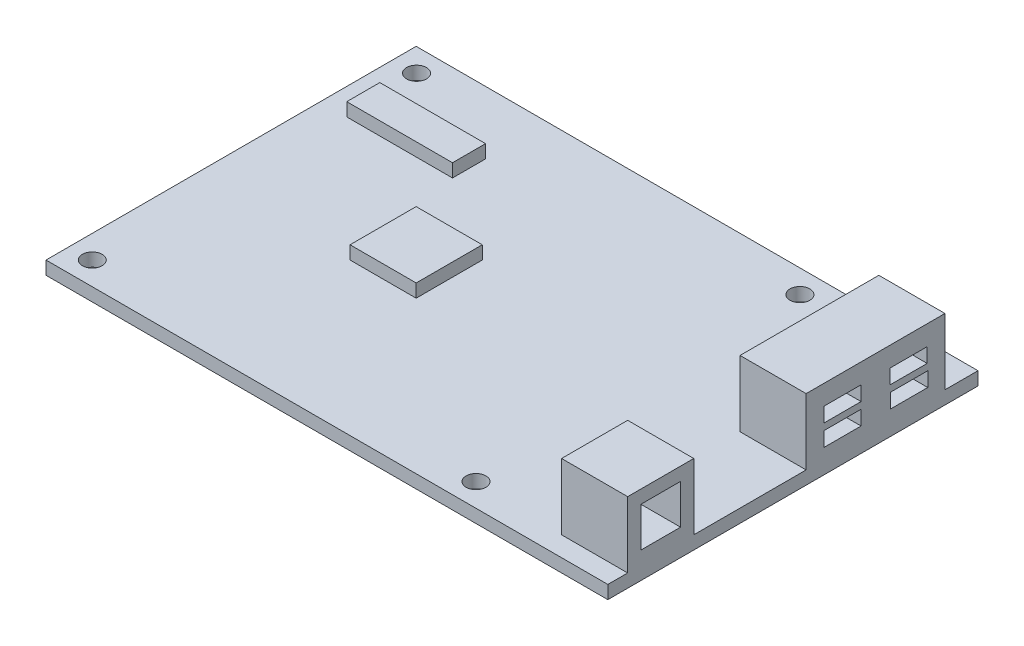
SolidWorks part; units mm, degrees
ref_plane "前视基准面" through (0, 0, 0) normal (0, 0, 1) x (1, 0, 0)
ref_plane "上视基准面" through (0, 0, 0) normal (0, 1, 0) x (1, 0, 0)
ref_plane "右视基准面" through (0, 0, 0) normal (1, 0, 0) x (0, 0, -1)
sketch "草图1" plane through (0, 0, 0) normal (0, 1, 0) x (1, 0, 0)
  line L1 (-42.5, 28) -> (42.5, 28)
  line L2 (-42.5, 28) -> (-42.5, -28)
  line L3 (-42.5, -28) -> (42.5, -28)
  line L4 (42.5, 28) -> (42.5, -28)
  line L5 (-42.5, 28) -> (42.5, -28) construction
  line L6 (-42.5, -28) -> (42.5, 28) construction
  circle A0 centre (-39, -24.5) radius 1.5
  circle A1 centre (-38.946, 24.5) radius 1.5
  circle A2 centre (19.054, 24.5) radius 1.5
  circle A3 centre (19.054, -24.5) radius 1.5
  point P0 (0, 0)
  point P16 (17.3531, 23.4403)
  point P17 (-165.7227, 76.68)
  point P18 (-164.177, 78.5691)
  point P19 (-38.9652, 22.1046)
  point P20 (19.2763, 23.8376)
  dimension "D6" = 3
  dimension "D7" = 3
  dimension "D9" = 49
  dimension "D10" = 3
  dimension "D13" = 3
  dimension "D1" = 85
  dimension "D2" = 56
  dimension "D3" = 3.5
  dimension "D4" = 49
  dimension "D5" = 3.5
  dimension "D8" = 58
  dimension "D11" = 3.5
  dimension "D12" = 0
  dimension "D14" = 38.946
extrude "凸台-拉伸1" add sketch "草图1" along normal blind 2
sketch "草图2" plane through (0, 2, 0) normal (0, 1, 0) x (1, 0, 0)
  line L0 (42.5, 28) -> (-42.5, 28) construction
  line L1 (-19.5, 5) -> (-9.5, 5)
  line L2 (-19.5, 5) -> (-19.5, -5)
  line L3 (-19.5, -5) -> (-9.5, -5)
  line L4 (-9.5, 5) -> (-9.5, -5)
  line L5 (-19.5, 5) -> (-9.5, -5) construction
  line L6 (-19.5, -5) -> (-9.5, 5) construction
  line L7 (-42.5, 28) -> (-42.5, -28) construction
  point P0 (-14.5, 0)
  dimension "D1" = 10
  dimension "D2" = 10
  dimension "D3" = 28
  dimension "D4" = 28
  dimension "D5" = 28
extrude "凸台-拉伸2" add sketch "草图2" along normal blind 2
sketch "草图3" plane through (0, 2, 0) normal (0, 1, 0) x (1, 0, 0)
  line L0 (42.5, -28) -> (42.5, 28) construction
  line L1 (32.5, 23) -> (42.5, 23)
  line L2 (32.5, 23) -> (32.5, 2)
  line L3 (32.5, 2) -> (42.5, 2)
  line L4 (42.5, 23) -> (42.5, 2)
  line L5 (32.5, 23) -> (42.5, 2) construction
  line L6 (32.5, 2) -> (42.5, 23) construction
  line L7 (-42.5, -28) -> (42.5, -28) construction
  line L8 (42.5, 28) -> (-42.5, 28) construction
  point P0 (37.5, 12.5)
  dimension "D1" = 10
  dimension "D2" = 30
  dimension "D3" = 5
extrude "凸台-拉伸3" add sketch "草图3" along normal blind 10
sketch "草图4" plane through (42.5, 0, 0) normal (1, 0, 0) x (0, 0, -1)
  line L1 (2, 12) -> (2, 2) construction
  line L2 (23, 12) -> (23, 2) construction
  line L5 (14, 10) -> (21, 3) construction
  line L6 (14, 3) -> (21, 10) construction
  line L11 (4, 10) -> (11, 3) construction
  line L12 (4, 3) -> (11, 10) construction
  line L14 (-28, 0) -> (28, 0) construction
  line L16 (4.71, 9) -> (10.31, 9)
  line L17 (4.71, 9) -> (4.71, 6.8)
  line L18 (4.71, 6.8) -> (10.31, 6.8)
  line L19 (10.31, 9) -> (10.31, 6.8)
  line L20 (4.71, 9) -> (10.31, 6.8) construction
  line L21 (4.71, 6.8) -> (10.31, 9) construction
  line L22 (10.31, 5.8) -> (4.71, 5.8)
  line L23 (10.31, 5.8) -> (10.31, 3.6)
  line L24 (10.31, 3.6) -> (4.71, 3.6)
  line L25 (4.71, 5.8) -> (4.71, 3.6)
  line L26 (10.31, 5.8) -> (4.71, 3.6) construction
  line L27 (10.31, 3.6) -> (4.71, 5.8) construction
  line L28 (14.71, 9) -> (20.31, 9)
  line L29 (14.71, 9) -> (14.71, 6.8)
  line L30 (14.71, 6.8) -> (20.31, 6.8)
  line L31 (20.31, 9) -> (20.31, 6.8)
  line L32 (14.71, 9) -> (20.31, 6.8) construction
  line L33 (14.71, 6.8) -> (20.31, 9) construction
  line L34 (14.8, 5.8) -> (20.4, 5.8)
  line L35 (14.8, 5.8) -> (14.8, 3.6)
  line L36 (14.8, 3.6) -> (20.4, 3.6)
  line L37 (20.4, 5.8) -> (20.4, 3.6)
  line L38 (14.8, 5.8) -> (20.4, 3.6) construction
  line L39 (14.8, 3.6) -> (20.4, 5.8) construction
  point P0 (17.5, 6.5)
  point P5 (7.5, 6.5)
  point P16 (7.51, 7.9)
  point P21 (7.51, 4.7)
  point P26 (17.51, 7.9)
  point P31 (17.6, 4.7)
  dimension "D3" = 7
  dimension "D4" = 7
  dimension "D5" = 7
  dimension "D6" = 7
  dimension "D7" = 2.71
  dimension "D8" = 2.71
  dimension "D9" = 5.6
  dimension "D10" = 2.2
  dimension "D11" = 5.6
  dimension "D12" = 2.2
  dimension "D13" = 1
  dimension "D14" = 5.6
  dimension "D15" = 2.69
  dimension "D16" = 2.6
  dimension "D17" = 2.2
  dimension "D18" = 3.6
  dimension "D19" = 3.6
  dimension "D20" = 2.2
  dimension "D22" = 1
  dimension "D23" = 5.6
extrude "切除-拉伸1" cut sketch "草图4" against normal blind 8
sketch "草图5" plane through (42.5, 0, 0) normal (1, 0, 0) x (0, 0, -1)
  line L0 (-28, 2) -> (2, 2) construction
  line L1 (-25, 12) -> (-15, 12)
  line L2 (-25, 12) -> (-25, 2)
  line L3 (-25, 2) -> (-15, 2)
  line L4 (-15, 12) -> (-15, 2)
  line L5 (-25, 12) -> (-15, 2) construction
  line L6 (-25, 2) -> (-15, 12) construction
  line L7 (-23, 10) -> (-17, 10)
  line L8 (-23, 10) -> (-23, 4)
  line L9 (-23, 4) -> (-17, 4)
  line L10 (-17, 10) -> (-17, 4)
  line L11 (-23, 10) -> (-17, 4) construction
  line L12 (-23, 4) -> (-17, 10) construction
  line L13 (2, 12) -> (2, 2) construction
  point P0 (-20, 7)
  point P5 (-20, 7)
  dimension "D1" = 0
  dimension "D2" = 2
  dimension "D3" = 10
  dimension "D4" = 10
  dimension "D5" = 17
extrude "凸台-拉伸4" add sketch "草图5" against normal blind 10
sketch "草图6" plane through (32.5, 0, 0) normal (-1, 0, 0) x (0, 0, 1)
  line L1 (17, 10) -> (23, 10)
  line L2 (17, 10) -> (17, 4)
  line L3 (17, 4) -> (23, 4)
  line L4 (23, 10) -> (23, 4)
  line L5 (17, 10) -> (23, 4) construction
  line L6 (17, 4) -> (23, 10) construction
  point P0 (20, 7)
  dimension "D1" = 6
extrude "凸台-拉伸6" add sketch "草图6" against normal blind 1
sketch "草图7" plane through (0, 2, 0) normal (0, 1, 0) x (1, 0, 0)
  line L0 (-42.5, 28) -> (-42.5, -28) construction
  line L1 (-38.5, 18.5) -> (-22.5, 18.5)
  line L2 (-38.5, 18.5) -> (-38.5, 13.5)
  line L3 (-38.5, 13.5) -> (-22.5, 13.5)
  line L4 (-22.5, 18.5) -> (-22.5, 13.5)
  line L5 (-38.5, 18.5) -> (-22.5, 13.5) construction
  line L6 (-38.5, 13.5) -> (-22.5, 18.5) construction
  line L7 (42.5, 28) -> (-42.5, 28) construction
  point P0 (-30.5, 16)
  dimension "D1" = 16
  dimension "D2" = 5
  dimension "D3" = 12
  dimension "D4" = 12
extrude "凸台-拉伸7" add sketch "草图7" along normal blind 2
